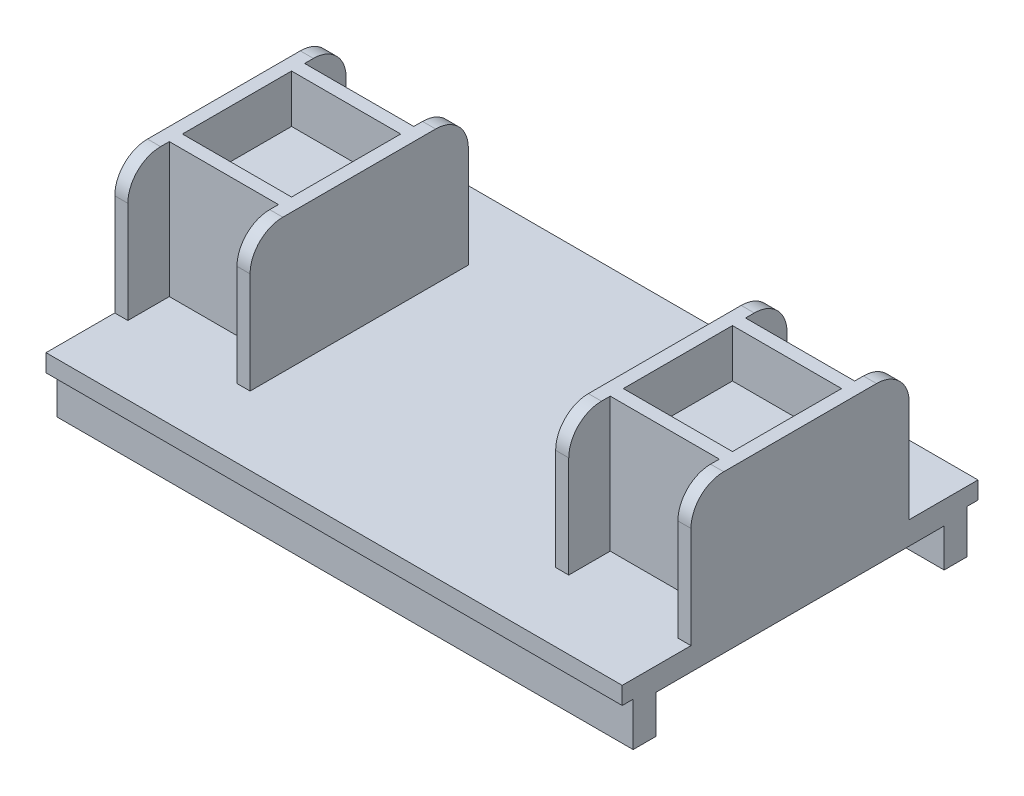
SolidWorks part; units mm, degrees
ref_plane "前视基准面" through (0, 0, 0) normal (0, 0, 1) x (1, 0, 0)
ref_plane "上视基准面" through (0, 0, 0) normal (0, 1, 0) x (1, 0, 0)
ref_plane "右视基准面" through (0, 0, 0) normal (1, 0, 0) x (0, 0, -1)
sketch "草图1" plane through (0, 0, 0) normal (0, 1, 0) x (1, 0, 0)
  line L0 (-1000, 0) -> (49000, 0) construction
  line L1 (-264, 163) -> (264, 163)
  line L2 (-264, 163) -> (-264, -163)
  line L3 (-264, -163) -> (264, -163)
  line L4 (264, 163) -> (264, -163)
  line L5 (0, -1000) -> (0, 49000) construction
  dimension "D1" = 528
  dimension "D2" = 326
extrude "凸台-拉伸1" add sketch "草图1" along normal blind 16
sketch "草图2" plane through (0, 0, 0) normal (0, -1, 0) x (1, 0, 0)
  line L0 (-264, -163) -> (-264, 163) construction
  line L1 (-264, 153) -> (264, 153)
  line L2 (-264, 153) -> (-264, 137)
  line L3 (-264, 137) -> (264, 137)
  line L4 (264, 153) -> (264, 137)
  line L5 (264, 163) -> (264, -163) construction
  line L6 (-1000, 0) -> (49000, 0) construction
  line L7 (-264, -137) -> (264, -137)
  line L8 (-264, -137) -> (-264, -153)
  line L9 (-264, -153) -> (264, -153)
  line L10 (264, -137) -> (264, -153)
  dimension "D1" = 16
  dimension "D2" = 16
  dimension "D3" = 306
extrude "凸台-拉伸2" add sketch "草图2" along normal blind 40
sketch "草图3" plane through (264, 0, 0) normal (1, 0, 0) x (0, 0, -1)
  line L0 (-137, -40) -> (-137, 0)
  line L1 (-137, 0) -> (137, 0)
  line L2 (137, 0) -> (137, -40)
  line L3 (137, -40) -> (132, -40)
  line L4 (132, -40) -> (132, -5)
  line L5 (132, -5) -> (-132, -5)
  line L6 (-132, -5) -> (-132, -40)
  line L7 (-132, -40) -> (-137, -40)
  dimension "D1" = 5
  dimension "D2" = 5
  dimension "D3" = 5
extrude "凸台-拉伸3" add sketch "草图3" against normal blind 528
sketch "草图4" plane through (-264, 0, 0) normal (-1, 0, 0) x (0, 0, 1)
  line L0 (-163, 16) -> (163, 16) construction
  line L1 (-70, 139) -> (70, 139)
  line L2 (-100, 109) -> (-100, 16)
  line L3 (-100, 16) -> (100, 16)
  line L4 (100, 109) -> (100, 16)
  arc A0 (100, 109) -> (70, 139) centre (70, 109) ccw
  arc A1 (-100, 109) -> (-70, 139) centre (-70, 109) cw
  point P9 (100, 139)
  dimension "D4" = 30
  dimension "D1" = 100
  dimension "D2" = 100
  dimension "D3" = 123
extrude "凸台-拉伸4" add sketch "草图4" against normal blind 12
pattern_linear "阵列(线性)1" count 2 spacing 112 along (1, 0, 0) of "凸台-拉伸4"
sketch "草图5" plane through (0, 16, 0) normal (0, 1, 0) x (1, 0, 0)
  line L0 (-252, 100) -> (-252, -100) construction
  line L1 (-252, 62) -> (-152, 62)
  line L2 (-252, 62) -> (-252, 50)
  line L3 (-252, 50) -> (-152, 50)
  line L4 (-152, 62) -> (-152, 50)
  line L5 (-152, -70) -> (-152, 70) construction
  line L6 (-1000, 0) -> (49000, 0) construction
  line L7 (-252, -50) -> (-152, -50)
  line L8 (-252, -50) -> (-252, -62)
  line L9 (-252, -62) -> (-152, -62)
  line L10 (-152, -50) -> (-152, -62)
  dimension "D1" = 12
  dimension "D2" = 12
  dimension "D3" = 124
extrude "凸台-拉伸5" add sketch "草图5" along normal blind 123
sketch "草图6" plane through (-152, 0, 0) normal (-1, 0, 0) x (0, 0, 1)
  line L0 (0, -1000) -> (0, 49000) construction
  line L1 (70, 139) -> (-70, 139) construction
  line L2 (-50, 95) -> (50, 95)
  line L3 (-50, 95) -> (-50, 83)
  line L4 (-50, 83) -> (50, 83)
  line L5 (50, 95) -> (50, 83)
  dimension "D1" = 12
  dimension "D2" = 44
  dimension "D3" = 100
extrude "凸台-拉伸6" add sketch "草图6" along normal blind 100
mirror "镜向2" about plane through (0, 0, 0) normal (1, 0, 0) of "凸台-拉伸6", "凸台-拉伸5", "阵列(线性)1", "凸台-拉伸4"
